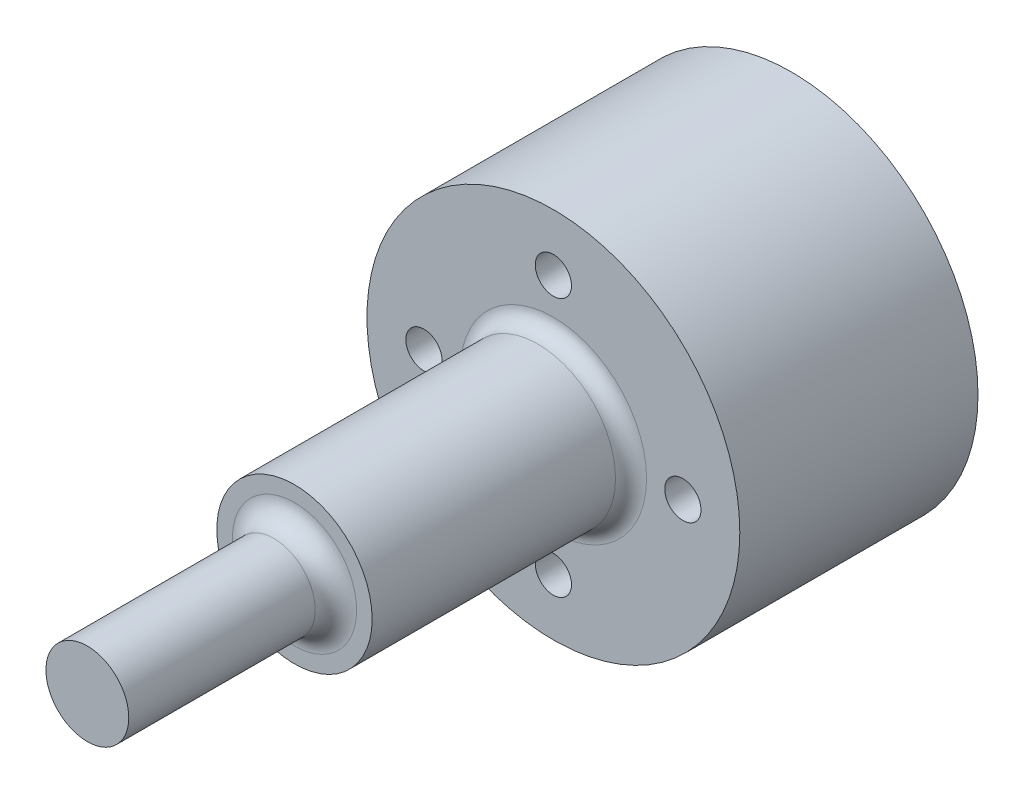
SolidWorks part; units mm, degrees
ref_plane "前视基准面" through (0, 0, 0) normal (0, 0, 1) x (1, 0, 0)
ref_plane "上视基准面" through (0, 0, 0) normal (0, 1, 0) x (1, 0, 0)
ref_plane "右视基准面" through (0, 0, 0) normal (1, 0, 0) x (0, 0, -1)
sketch "草图1" plane through (0, 0, 0) normal (0, 0, 1) x (1, 0, 0)
  circle A0 centre (0, 0) radius 15
  circle A1 centre (0, 0) radius 18
  dimension "D1" = 30
  dimension "D2" = 36
extrude "凸台-拉伸1" add sketch "草图1" along normal blind 20
sketch "草图2" plane through (0, 0, 20) normal (0, 0, 1) x (1, 0, 0)
  circle A1 centre (0, 0) radius 18
extrude "凸台-拉伸2" add sketch "草图2" along normal blind 3
sketch "草图3" plane through (0, 0, 23) normal (0, 0, 1) x (1, 0, 0)
  circle A0 centre (0, 0) radius 4.5
  circle A1 centre (0, 0) radius 7.5
  dimension "D1" = 9
  dimension "D2" = 15
extrude "凸台-拉伸3" add sketch "草图3" along normal blind 20
sketch "草图4" plane through (0, 0, 23) normal (0, 0, 1) x (1, 0, 0)
  circle A0 centre (0, 0) radius 4.5
extrude "切除-拉伸1" cut sketch "草图4" against normal blind 20
sketch "草图5" plane through (0, 0, 43) normal (0, 0, 1) x (1, 0, 0)
  circle A1 centre (0, 0) radius 7.5
extrude "凸台-拉伸4" add sketch "草图5" along normal blind 5
sketch "草图6" plane through (0, 0, 48) normal (0, 0, 1) x (1, 0, 0)
  circle A0 centre (0, 0) radius 4
  dimension "D1" = 8
extrude "凸台-拉伸5" add sketch "草图6" along normal blind 20
sketch "草图7" plane through (0, 0, 23) normal (0, 0, 1) x (1, 0, 0)
  circle A0 centre (0, 0) radius 12.5 construction
  circle A1 centre (0, 12.5) radius 1.75
  circle A2 centre (12.5, 0) radius 1.75
  circle A3 centre (0, -12.5) radius 1.75
  circle A4 centre (-12.5, 0) radius 1.75
  dimension "D2" = 3.5
  dimension "D3" = 25
  dimension "D1" = 4
extrude "切除-拉伸2" cut sketch "草图7" against normal blind 15
fillet "圆角1" radius 2 1 edges at (4, 0, 48)
fillet "圆角2" radius 1.5 1 edges at (7.5, 0, 23)
